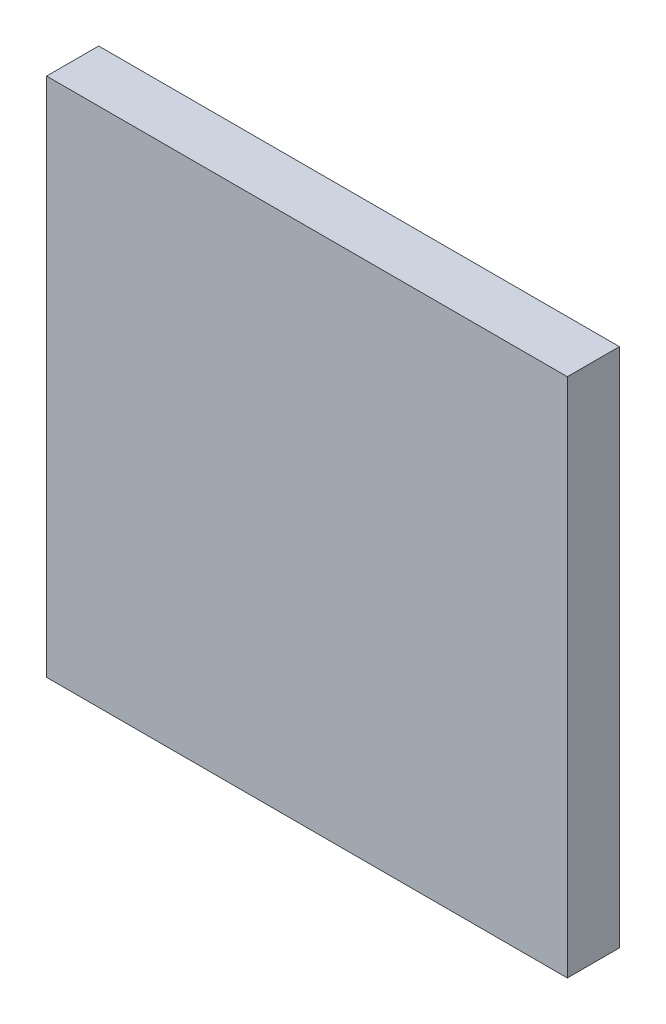
SolidWorks part; units mm, degrees
ref_plane "Front Plane" through (0, 0, 0) normal (0, 0, 1) x (1, 0, 0)
ref_plane "Top Plane" through (0, 0, 0) normal (0, 1, 0) x (1, 0, 0)
ref_plane "Right Plane" through (0, 0, 0) normal (1, 0, 0) x (0, 0, -1)
sketch "Sketch1" plane through (0, 0, 0) normal (0, 0, 1) x (1, 0, 0)
  line L1 (5, -5) -> (-5, -5)
  line L2 (5, -5) -> (5, 5)
  line L3 (5, 5) -> (-5, 5)
  line L4 (-5, -5) -> (-5, 5)
  line L5 (5, -5) -> (-5, 5) construction
  line L6 (5, 5) -> (-5, -5) construction
  point P0 (0, 0)
  dimension "D1" = 10
  dimension "D2" = 10
extrude "Boss-Extrude1" add sketch "Sketch1" along normal blind 1
